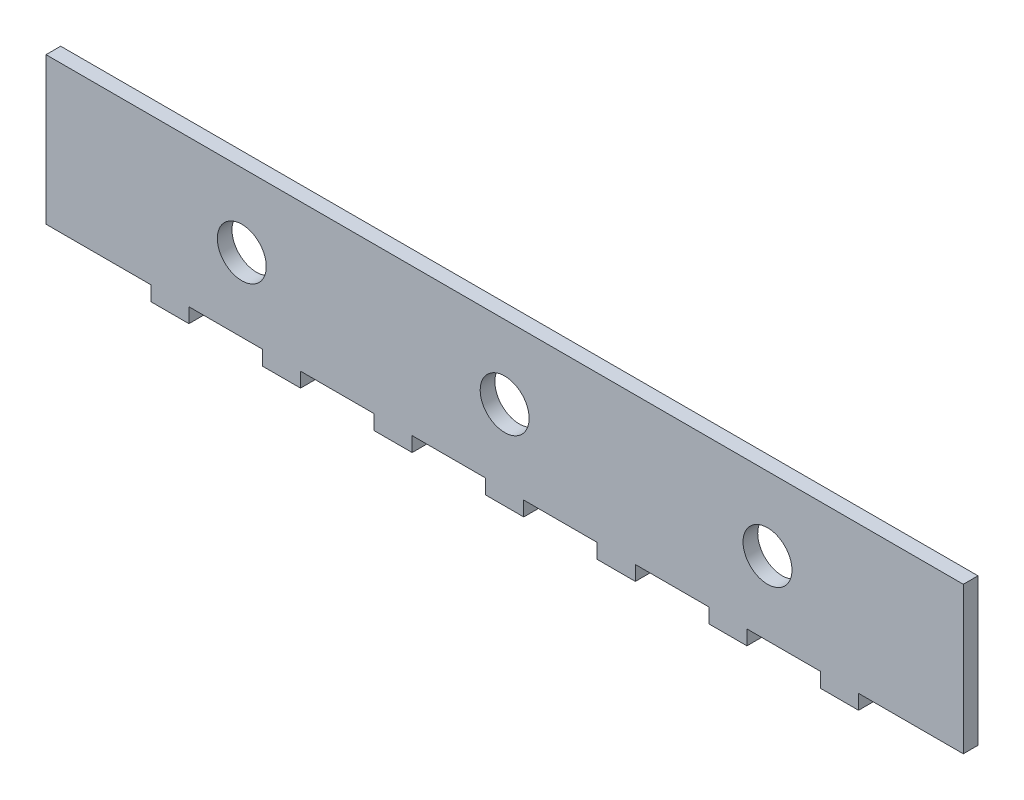
SolidWorks part; units mm, degrees
material "Oak"
ref_plane "Front Plane" through (0, 0, 0) normal (0, 0, 1) x (1, 0, 0)
ref_plane "Top Plane" through (0, 0, 0) normal (0, 1, 0) x (1, 0, 0)
ref_plane "Right Plane" through (0, 0, 0) normal (1, 0, 0) x (0, 0, -1)
sketch "Sketch1" plane through (0, 0, 0) normal (0, 0, 1) x (1, 0, 0)
  line L1 (-93.7, 15) -> (93.7, 15)
  line L2 (-93.7, 15) -> (-93.7, -15)
  line L3 (-93.7, -15) -> (93.7, -15)
  line L4 (93.7, 15) -> (93.7, -15)
  dimension "D1" = 30
  dimension "D2" = 187.4
  dimension "D3" = 15
  dimension "D4" = 93.7
extrude "Boss-Extrude1" add sketch "Sketch1" along normal blind 3
sketch "Sketch2" plane through (0, -15, 0) normal (0, -1, 0) x (1, 0, 0)
  line L0 (-93.7, 3) -> (93.7, 3) construction
  line L1 (-3.9, 3) -> (3.9, 3)
  line L2 (-3.9, 3) -> (-3.9, 0)
  line L3 (-3.9, 0) -> (3.9, 0)
  line L4 (3.9, 3) -> (3.9, 0)
  line L5 (55, 0) -> (-55, 0) construction
  line L6 (0, -55) -> (0, 55) construction
  dimension "D1" = 7.8
  dimension "D2" = 3.9
extrude "Boss-Extrude2" add sketch "Sketch2" along normal blind 3
pattern_linear "LPattern2" count 4 spacing 22.8 along (1, 0, 0) count 4 spacing 22.8 along (-1, 0, 0) of "Boss-Extrude2"
sketch "Sketch3" plane through (0, 0, 0) normal (0, 0, -1) x (-1, 0, 0)
  line L1 (-49.5, -15) -> (-64.5, -15) construction
  line L2 (-93.7, -15) -> (-93.7, 15) construction
  line L3 (41.7, -15) -> (26.7, -15) construction
  line L4 (93.7, 15) -> (93.7, -15) construction
  circle A0 centre (0, 0) radius 5
  circle A1 centre (-53.7, 0) radius 5
  circle A2 centre (53.7, 0) radius 5
  dimension "D1" = 10
  dimension "D2" = 10
  dimension "D7" = 10
  dimension "D3" = 15
  dimension "D4" = 40
  dimension "D5" = 15
  dimension "D6" = 40
extrude "Cut-Extrude1" cut sketch "Sketch3" against normal through all
